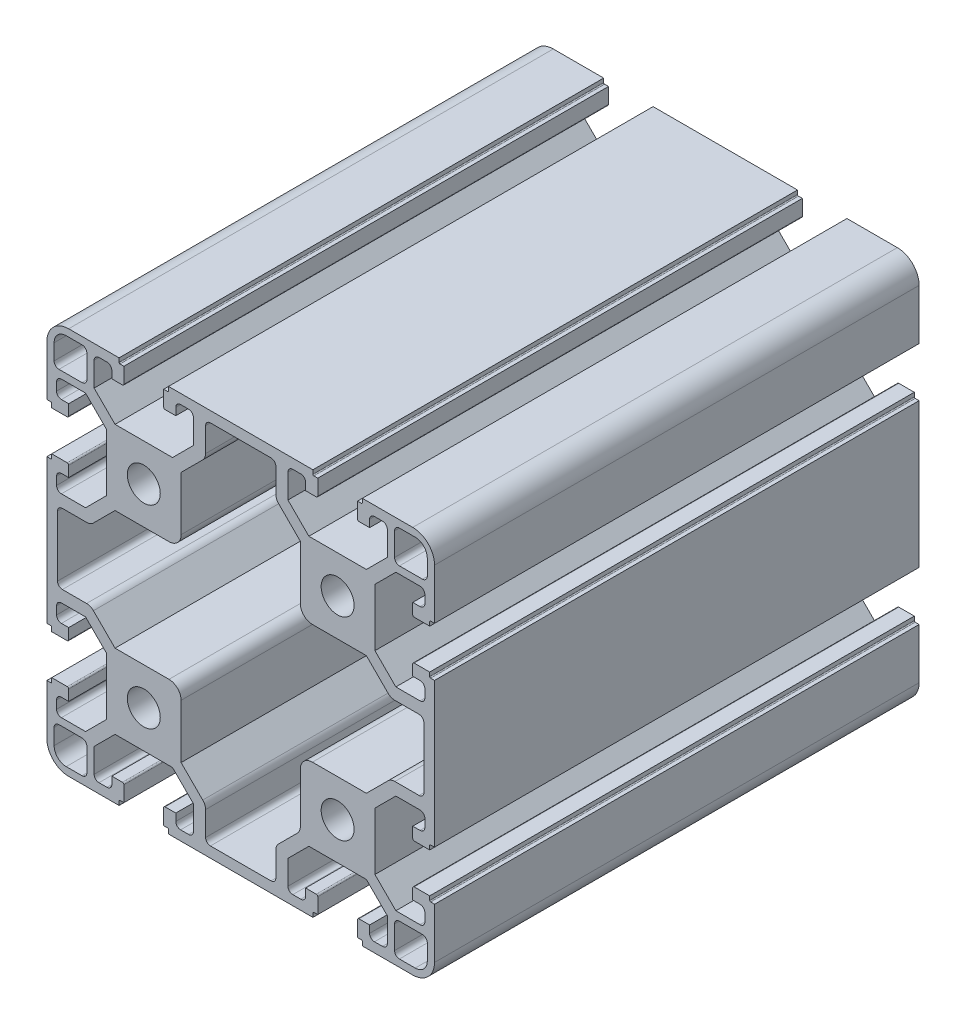
SolidWorks part; units mm, degrees
ref_plane "前视基准面" through (0, 0, 0) normal (0, 0, 1) x (1, 0, 0)
ref_plane "上视基准面" through (0, 0, 0) normal (0, 1, 0) x (1, 0, 0)
ref_plane "右视基准面" through (0, 0, 0) normal (1, 0, 0) x (0, 0, -1)
sketch "草图1" plane through (0, 0, 0) normal (0, 0, 1) x (1, 0, 0)
  line L0 (33.5347, -31.1296) -> (38.2887, -31.1296)
  line L1 (39.2887, -32.1296) -> (39.2887, -35.3836)
  line L2 (36.7887, -37.8836) -> (33.5347, -37.8836)
  line L3 (32.5347, -36.8836) -> (32.5347, -32.1296)
  line L4 (-30.9653, -32.1296) -> (-30.9653, -36.8836)
  line L5 (-31.9653, -37.8836) -> (-35.2193, -37.8836)
  line L6 (-37.7193, -35.3836) -> (-37.7193, -32.1296)
  line L7 (-36.7193, -31.1296) -> (-31.9653, -31.1296)
  line L8 (32.5347, 33.3704) -> (32.5347, 38.1244)
  line L9 (33.5347, 39.1244) -> (36.7887, 39.1244)
  line L10 (39.2887, 36.6244) -> (39.2887, 33.3704)
  line L11 (38.2887, 32.3704) -> (33.5347, 32.3704)
  line L12 (-31.9653, 32.3704) -> (-36.7193, 32.3704)
  line L13 (-37.7193, 33.3704) -> (-37.7193, 36.6244)
  line L14 (-35.2193, 39.1244) -> (-31.9653, 39.1244)
  line L15 (-30.9653, 38.1244) -> (-30.9653, 33.3704)
  line L16 (-11.5153, 26.5526) -> (-7.0511, 31.0168)
  line L17 (-6.4653, 32.4311) -> (-6.4653, 37.4204)
  line L18 (-5.4653, 38.4204) -> (7.0347, 38.4204)
  line L19 (8.0347, 37.4204) -> (8.0347, 32.4311)
  line L20 (8.6205, 31.0168) -> (13.0847, 26.5526)
  line L21 (13.0847, 26.5526) -> (13.0847, 15.4204)
  line L22 (15.5847, 12.9204) -> (26.717, 12.9204)
  line L23 (26.717, 12.9204) -> (31.1812, 8.4562)
  line L24 (32.5954, 7.8704) -> (37.5847, 7.8704)
  line L25 (38.5847, 6.8704) -> (38.5847, -5.6296)
  line L26 (37.5847, -6.6296) -> (32.5954, -6.6296)
  line L27 (31.1812, -7.2154) -> (26.717, -11.6796)
  line L28 (26.717, -11.6796) -> (15.5847, -11.6796)
  line L29 (13.0847, -14.1796) -> (13.0847, -24.4834)
  line L30 (12.4989, -25.8976) -> (8.6205, -29.776)
  line L31 (8.0347, -31.1903) -> (8.0347, -36.1796)
  line L32 (7.0347, -37.1796) -> (-5.4653, -37.1796)
  line L33 (-6.4653, -36.1796) -> (-6.4653, -31.1903)
  line L34 (-7.0511, -29.776) -> (-11.5153, -25.3118)
  line L35 (-11.5153, -25.3118) -> (-11.5153, -14.1796)
  line L36 (-14.0153, -11.6796) -> (-25.1475, -11.6796)
  line L37 (-25.1475, -11.6796) -> (-29.6117, -7.2154)
  line L38 (-31.0259, -6.6296) -> (-36.0153, -6.6296)
  line L39 (-37.0153, -5.6296) -> (-37.0153, 6.8704)
  line L40 (-36.0153, 7.8704) -> (-31.0259, 7.8704)
  line L41 (-29.6117, 8.4562) -> (-25.1475, 12.9204)
  line L42 (-25.1475, 12.9204) -> (-14.0153, 12.9204)
  line L43 (-11.5153, 15.4204) -> (-11.5153, 26.5526)
  line L44 (28.4847, 26.5526) -> (32.8025, 30.8704)
  line L45 (32.8025, 30.8704) -> (37.7847, 30.8704)
  line L46 (38.7847, 29.8704) -> (38.7847, 28.2204)
  line L47 (37.7847, 27.2204) -> (36.2847, 27.2204)
  line L48 (36.2847, 27.2204) -> (36.2847, 25.0204)
  line L49 (36.5847, 24.7204) -> (39.7847, 24.7204)
  line L50 (39.7847, 24.7204) -> (39.7847, 25.5204)
  line L51 (39.9847, 25.7204) -> (40.7847, 25.7204)
  line L52 (40.7847, 25.7204) -> (40.7847, 36.1204)
  line L53 (36.2847, 40.6204) -> (25.8847, 40.6204)
  line L54 (25.8847, 40.6204) -> (25.8847, 39.8204)
  line L55 (25.6847, 39.6204) -> (24.8847, 39.6204)
  line L56 (24.8847, 39.6204) -> (24.8847, 36.4204)
  line L57 (25.1847, 36.1204) -> (27.3847, 36.1204)
  line L58 (27.3847, 36.1204) -> (27.3847, 37.6204)
  line L59 (28.3847, 38.6204) -> (30.0347, 38.6204)
  line L60 (31.0347, 37.6204) -> (31.0347, 32.6382)
  line L61 (31.0347, 32.6382) -> (26.717, 28.3204)
  line L62 (26.717, 28.3204) -> (14.8525, 28.3204)
  line L63 (14.8525, 28.3204) -> (10.5347, 32.6382)
  line L64 (10.5347, 32.6382) -> (10.5347, 37.6204)
  line L65 (11.5347, 38.6204) -> (13.1847, 38.6204)
  line L66 (14.1847, 37.6204) -> (14.1847, 36.1204)
  line L67 (14.1847, 36.1204) -> (16.3847, 36.1204)
  line L68 (16.6847, 36.4204) -> (16.6847, 39.6204)
  line L69 (16.6847, 39.6204) -> (15.8847, 39.6204)
  line L70 (15.6847, 39.8204) -> (15.6847, 40.6204)
  line L71 (15.6847, 40.6204) -> (5.2847, 40.6204)
  line L72 (5.2847, 40.6204) -> (-3.7153, 40.6204)
  line L73 (-3.7153, 40.6204) -> (-14.1153, 40.6204)
  line L74 (-14.1153, 40.6204) -> (-14.1153, 39.8204)
  line L75 (-14.3153, 39.6204) -> (-15.1153, 39.6204)
  line L76 (-15.1153, 39.6204) -> (-15.1153, 36.4204)
  line L77 (-14.8153, 36.1204) -> (-12.6153, 36.1204)
  line L78 (-12.6153, 36.1204) -> (-12.6153, 37.6204)
  line L79 (-11.6153, 38.6204) -> (-9.9653, 38.6204)
  line L80 (-8.9653, 37.6204) -> (-8.9653, 32.6382)
  line L81 (-8.9653, 32.6382) -> (-13.283, 28.3204)
  line L82 (-13.283, 28.3204) -> (-25.1475, 28.3204)
  line L83 (-25.1475, 28.3204) -> (-29.4653, 32.6382)
  line L84 (-29.4653, 32.6382) -> (-29.4653, 37.6204)
  line L85 (-28.4653, 38.6204) -> (-26.8153, 38.6204)
  line L86 (-25.8153, 37.6204) -> (-25.8153, 36.1204)
  line L87 (-25.8153, 36.1204) -> (-23.6153, 36.1204)
  line L88 (-23.3153, 36.4204) -> (-23.3153, 39.6204)
  line L89 (-23.3153, 39.6204) -> (-24.1153, 39.6204)
  line L90 (-24.3153, 39.8204) -> (-24.3153, 40.6204)
  line L91 (-24.3153, 40.6204) -> (-34.7153, 40.6204)
  line L92 (-39.2153, 36.1204) -> (-39.2153, 25.7204)
  line L93 (-39.2153, 25.7204) -> (-38.4153, 25.7204)
  line L94 (-38.2153, 25.5204) -> (-38.2153, 24.7204)
  line L95 (-38.2153, 24.7204) -> (-35.0153, 24.7204)
  line L96 (-34.7153, 25.0204) -> (-34.7153, 27.2204)
  line L97 (-34.7153, 27.2204) -> (-36.2153, 27.2204)
  line L98 (-37.2153, 28.2204) -> (-37.2153, 29.8704)
  line L99 (-36.2153, 30.8704) -> (-31.233, 30.8704)
  line L100 (-31.233, 30.8704) -> (-26.9153, 26.5526)
  line L101 (-26.9153, 26.5526) -> (-26.9153, 14.6882)
  line L102 (-26.9153, 14.6882) -> (-31.233, 10.3704)
  line L103 (-31.233, 10.3704) -> (-36.2153, 10.3704)
  line L104 (-37.2153, 11.3704) -> (-37.2153, 13.0204)
  line L105 (-36.2153, 14.0204) -> (-34.7153, 14.0204)
  line L106 (-34.7153, 14.0204) -> (-34.7153, 16.2204)
  line L107 (-35.0153, 16.5204) -> (-38.2153, 16.5204)
  line L108 (-38.2153, 16.5204) -> (-38.2153, 15.7204)
  line L109 (-38.4153, 15.5204) -> (-39.2153, 15.5204)
  line L110 (-39.2153, 15.5204) -> (-39.2153, 5.1204)
  line L111 (-39.2153, 5.1204) -> (-39.2153, -3.8796)
  line L112 (-39.2153, -3.8796) -> (-39.2153, -14.2796)
  line L113 (-39.2153, -14.2796) -> (-38.4153, -14.2796)
  line L114 (-38.2153, -14.4796) -> (-38.2153, -15.2796)
  line L115 (-38.2153, -15.2796) -> (-35.0153, -15.2796)
  line L116 (-34.7153, -14.9796) -> (-34.7153, -12.7796)
  line L117 (-34.7153, -12.7796) -> (-36.2153, -12.7796)
  line L118 (-37.2153, -11.7796) -> (-37.2153, -10.1296)
  line L119 (-36.2153, -9.1296) -> (-31.233, -9.1296)
  line L120 (-31.233, -9.1296) -> (-26.9153, -13.4474)
  line L121 (-26.9153, -13.4474) -> (-26.9153, -25.3118)
  line L122 (-26.9153, -25.3118) -> (-31.233, -29.6296)
  line L123 (-31.233, -29.6296) -> (-36.2153, -29.6296)
  line L124 (-37.2153, -28.6296) -> (-37.2153, -26.9796)
  line L125 (-36.2153, -25.9796) -> (-34.7153, -25.9796)
  line L126 (-34.7153, -25.9796) -> (-34.7153, -23.7796)
  line L127 (-35.0153, -23.4796) -> (-38.2153, -23.4796)
  line L128 (-38.2153, -23.4796) -> (-38.2153, -24.2796)
  line L129 (-38.4153, -24.4796) -> (-39.2153, -24.4796)
  line L130 (-39.2153, -24.4796) -> (-39.2153, -34.8796)
  line L131 (-34.7153, -39.3796) -> (-24.3153, -39.3796)
  line L132 (-24.3153, -39.3796) -> (-24.3153, -38.5796)
  line L133 (-24.1153, -38.3796) -> (-23.3153, -38.3796)
  line L134 (-23.3153, -38.3796) -> (-23.3153, -35.1796)
  line L135 (-23.6153, -34.8796) -> (-25.8153, -34.8796)
  line L136 (-25.8153, -34.8796) -> (-25.8153, -36.3796)
  line L137 (-26.8153, -37.3796) -> (-28.4653, -37.3796)
  line L138 (-29.4653, -36.3796) -> (-29.4653, -31.3974)
  line L139 (-29.4653, -31.3974) -> (-25.1475, -27.0796)
  line L140 (-25.1475, -27.0796) -> (-13.283, -27.0796)
  line L141 (-13.283, -27.0796) -> (-8.9653, -31.3974)
  line L142 (-8.9653, -31.3974) -> (-8.9653, -36.3796)
  line L143 (-9.9653, -37.3796) -> (-11.6153, -37.3796)
  line L144 (-12.6153, -36.3796) -> (-12.6153, -34.8796)
  line L145 (-12.6153, -34.8796) -> (-14.8153, -34.8796)
  line L146 (-15.1153, -35.1796) -> (-15.1153, -38.3796)
  line L147 (-15.1153, -38.3796) -> (-14.3153, -38.3796)
  line L148 (-14.1153, -38.5796) -> (-14.1153, -39.3796)
  line L149 (-14.1153, -39.3796) -> (-3.7153, -39.3796)
  line L150 (-3.7153, -39.3796) -> (5.2847, -39.3796)
  line L151 (5.2847, -39.3796) -> (15.6847, -39.3796)
  line L152 (15.6847, -39.3796) -> (15.6847, -38.5796)
  line L153 (15.8847, -38.3796) -> (16.6847, -38.3796)
  line L154 (16.6847, -38.3796) -> (16.6847, -35.1796)
  line L155 (16.3847, -34.8796) -> (14.1847, -34.8796)
  line L156 (14.1847, -34.8796) -> (14.1847, -36.3796)
  line L157 (13.1847, -37.3796) -> (11.5347, -37.3796)
  line L158 (10.5347, -36.3796) -> (10.5347, -31.3974)
  line L159 (10.5347, -31.3974) -> (14.8525, -27.0796)
  line L160 (14.8525, -27.0796) -> (26.717, -27.0796)
  line L161 (26.717, -27.0796) -> (31.0347, -31.3974)
  line L162 (31.0347, -31.3974) -> (31.0347, -36.3796)
  line L163 (30.0347, -37.3796) -> (28.3847, -37.3796)
  line L164 (27.3847, -36.3796) -> (27.3847, -34.8796)
  line L165 (27.3847, -34.8796) -> (25.1847, -34.8796)
  line L166 (24.8847, -35.1796) -> (24.8847, -38.3796)
  line L167 (24.8847, -38.3796) -> (25.6847, -38.3796)
  line L168 (25.8847, -38.5796) -> (25.8847, -39.3796)
  line L169 (25.8847, -39.3796) -> (36.2847, -39.3796)
  line L170 (40.7847, -34.8796) -> (40.7847, -24.4796)
  line L171 (40.7847, -24.4796) -> (39.9847, -24.4796)
  line L172 (39.7847, -24.2796) -> (39.7847, -23.4796)
  line L173 (39.7847, -23.4796) -> (36.5847, -23.4796)
  line L174 (36.2847, -23.7796) -> (36.2847, -25.9796)
  line L175 (36.2847, -25.9796) -> (37.7847, -25.9796)
  line L176 (38.7847, -26.9796) -> (38.7847, -28.6296)
  line L177 (37.7847, -29.6296) -> (32.8025, -29.6296)
  line L178 (32.8025, -29.6296) -> (28.4847, -25.3118)
  line L179 (28.4847, -25.3118) -> (28.4847, -13.4474)
  line L180 (28.4847, -13.4474) -> (32.8025, -9.1296)
  line L181 (32.8025, -9.1296) -> (37.7847, -9.1296)
  line L182 (38.7847, -10.1296) -> (38.7847, -11.7796)
  line L183 (37.7847, -12.7796) -> (36.2847, -12.7796)
  line L184 (36.2847, -12.7796) -> (36.2847, -14.9796)
  line L185 (36.5847, -15.2796) -> (39.7847, -15.2796)
  line L186 (39.7847, -15.2796) -> (39.7847, -14.4796)
  line L187 (39.9847, -14.2796) -> (40.7847, -14.2796)
  line L188 (40.7847, -14.2796) -> (40.7847, -3.8796)
  line L189 (40.7847, -3.8796) -> (40.7847, 5.1204)
  line L190 (40.7847, 5.1204) -> (40.7847, 15.5204)
  line L191 (40.7847, 15.5204) -> (39.9847, 15.5204)
  line L192 (39.7847, 15.7204) -> (39.7847, 16.5204)
  line L193 (39.7847, 16.5204) -> (36.5847, 16.5204)
  line L194 (36.2847, 16.2204) -> (36.2847, 14.0204)
  line L195 (36.2847, 14.0204) -> (37.7847, 14.0204)
  line L196 (38.7847, 13.0204) -> (38.7847, 11.3704)
  line L197 (37.7847, 10.3704) -> (32.8025, 10.3704)
  line L198 (32.8025, 10.3704) -> (28.4847, 14.6882)
  line L199 (28.4847, 14.6882) -> (28.4847, 26.5526)
  arc A0 (39.2887, -32.1296) -> (38.2887, -31.1296) centre (38.2887, -32.1296) ccw
  arc A1 (36.7887, -37.8836) -> (39.2887, -35.3836) centre (36.7887, -35.3836) ccw
  arc A2 (32.5347, -36.8836) -> (33.5347, -37.8836) centre (33.5347, -36.8836) ccw
  arc A3 (33.5347, -31.1296) -> (32.5347, -32.1296) centre (33.5347, -32.1296) ccw
  arc A4 (-31.9653, -37.8836) -> (-30.9653, -36.8836) centre (-31.9653, -36.8836) ccw
  arc A5 (-37.7193, -35.3836) -> (-35.2193, -37.8836) centre (-35.2193, -35.3836) ccw
  arc A6 (-36.7193, -31.1296) -> (-37.7193, -32.1296) centre (-36.7193, -32.1296) ccw
  arc A7 (-30.9653, -32.1296) -> (-31.9653, -31.1296) centre (-31.9653, -32.1296) ccw
  circle A8 centre (20.7847, -19.3796) radius 3.4
  arc A9 (33.5347, 39.1244) -> (32.5347, 38.1244) centre (33.5347, 38.1244) ccw
  arc A10 (39.2887, 36.6244) -> (36.7887, 39.1244) centre (36.7887, 36.6244) ccw
  arc A11 (38.2887, 32.3704) -> (39.2887, 33.3704) centre (38.2887, 33.3704) ccw
  arc A12 (32.5347, 33.3704) -> (33.5347, 32.3704) centre (33.5347, 33.3704) ccw
  circle A13 centre (-19.2153, -19.3796) radius 3.4
  circle A14 centre (20.7847, 20.6204) radius 3.4
  arc A15 (-37.7193, 33.3704) -> (-36.7193, 32.3704) centre (-36.7193, 33.3704) ccw
  arc A16 (-35.2193, 39.1244) -> (-37.7193, 36.6244) centre (-35.2193, 36.6244) ccw
  arc A17 (-30.9653, 38.1244) -> (-31.9653, 39.1244) centre (-31.9653, 38.1244) ccw
  arc A18 (-31.9653, 32.3704) -> (-30.9653, 33.3704) centre (-31.9653, 33.3704) ccw
  circle A19 centre (-19.2153, 20.6204) radius 3.4
  arc A20 (-7.0511, 31.0168) -> (-6.4653, 32.4311) centre (-8.4653, 32.4311) ccw
  arc A21 (-5.4653, 38.4204) -> (-6.4653, 37.4204) centre (-5.4653, 37.4204) ccw
  arc A22 (8.0347, 37.4204) -> (7.0347, 38.4204) centre (7.0347, 37.4204) ccw
  arc A23 (8.0347, 32.4311) -> (8.6205, 31.0168) centre (10.0347, 32.4311) ccw
  arc A24 (13.0847, 15.4204) -> (15.5847, 12.9204) centre (15.5847, 15.4204) ccw
  arc A25 (31.1812, 8.4562) -> (32.5954, 7.8704) centre (32.5954, 9.8704) ccw
  arc A26 (38.5847, 6.8704) -> (37.5847, 7.8704) centre (37.5847, 6.8704) ccw
  arc A27 (37.5847, -6.6296) -> (38.5847, -5.6296) centre (37.5847, -5.6296) ccw
  arc A28 (32.5954, -6.6296) -> (31.1812, -7.2154) centre (32.5954, -8.6296) ccw
  arc A29 (15.5847, -11.6796) -> (13.0847, -14.1796) centre (15.5847, -14.1796) ccw
  arc A30 (12.4989, -25.8976) -> (13.0847, -24.4834) centre (11.0847, -24.4834) ccw
  arc A31 (8.6205, -29.776) -> (8.0347, -31.1903) centre (10.0347, -31.1903) ccw
  arc A32 (7.0347, -37.1796) -> (8.0347, -36.1796) centre (7.0347, -36.1796) ccw
  arc A33 (-6.4653, -36.1796) -> (-5.4653, -37.1796) centre (-5.4653, -36.1796) ccw
  arc A34 (-6.4653, -31.1903) -> (-7.0511, -29.776) centre (-8.4653, -31.1903) ccw
  arc A35 (-11.5153, -14.1796) -> (-14.0153, -11.6796) centre (-14.0153, -14.1796) ccw
  arc A36 (-29.6117, -7.2154) -> (-31.0259, -6.6296) centre (-31.0259, -8.6296) ccw
  arc A37 (-37.0153, -5.6296) -> (-36.0153, -6.6296) centre (-36.0153, -5.6296) ccw
  arc A38 (-36.0153, 7.8704) -> (-37.0153, 6.8704) centre (-36.0153, 6.8704) ccw
  arc A39 (-31.0259, 7.8704) -> (-29.6117, 8.4562) centre (-31.0259, 9.8704) ccw
  arc A40 (-14.0153, 12.9204) -> (-11.5153, 15.4204) centre (-14.0153, 15.4204) ccw
  arc A41 (38.7847, 29.8704) -> (37.7847, 30.8704) centre (37.7847, 29.8704) ccw
  arc A42 (37.7847, 27.2204) -> (38.7847, 28.2204) centre (37.7847, 28.2204) ccw
  arc A43 (36.2847, 25.0204) -> (36.5847, 24.7204) centre (36.5847, 25.0204) ccw
  arc A44 (39.9847, 25.7204) -> (39.7847, 25.5204) centre (39.9847, 25.5204) ccw
  arc A45 (40.7847, 36.1204) -> (36.2847, 40.6204) centre (36.2847, 36.1204) ccw
  arc A46 (25.6847, 39.6204) -> (25.8847, 39.8204) centre (25.6847, 39.8204) ccw
  arc A47 (24.8847, 36.4204) -> (25.1847, 36.1204) centre (25.1847, 36.4204) ccw
  arc A48 (28.3847, 38.6204) -> (27.3847, 37.6204) centre (28.3847, 37.6204) ccw
  arc A49 (31.0347, 37.6204) -> (30.0347, 38.6204) centre (30.0347, 37.6204) ccw
  arc A50 (11.5347, 38.6204) -> (10.5347, 37.6204) centre (11.5347, 37.6204) ccw
  arc A51 (14.1847, 37.6204) -> (13.1847, 38.6204) centre (13.1847, 37.6204) ccw
  arc A52 (16.3847, 36.1204) -> (16.6847, 36.4204) centre (16.3847, 36.4204) ccw
  arc A53 (15.6847, 39.8204) -> (15.8847, 39.6204) centre (15.8847, 39.8204) ccw
  arc A54 (-14.3153, 39.6204) -> (-14.1153, 39.8204) centre (-14.3153, 39.8204) ccw
  arc A55 (-15.1153, 36.4204) -> (-14.8153, 36.1204) centre (-14.8153, 36.4204) ccw
  arc A56 (-11.6153, 38.6204) -> (-12.6153, 37.6204) centre (-11.6153, 37.6204) ccw
  arc A57 (-8.9653, 37.6204) -> (-9.9653, 38.6204) centre (-9.9653, 37.6204) ccw
  arc A58 (-28.4653, 38.6204) -> (-29.4653, 37.6204) centre (-28.4653, 37.6204) ccw
  arc A59 (-25.8153, 37.6204) -> (-26.8153, 38.6204) centre (-26.8153, 37.6204) ccw
  arc A60 (-23.6153, 36.1204) -> (-23.3153, 36.4204) centre (-23.6153, 36.4204) ccw
  arc A61 (-24.3153, 39.8204) -> (-24.1153, 39.6204) centre (-24.1153, 39.8204) ccw
  arc A62 (-34.7153, 40.6204) -> (-39.2153, 36.1204) centre (-34.7153, 36.1204) ccw
  arc A63 (-38.2153, 25.5204) -> (-38.4153, 25.7204) centre (-38.4153, 25.5204) ccw
  arc A64 (-35.0153, 24.7204) -> (-34.7153, 25.0204) centre (-35.0153, 25.0204) ccw
  arc A65 (-37.2153, 28.2204) -> (-36.2153, 27.2204) centre (-36.2153, 28.2204) ccw
  arc A66 (-36.2153, 30.8704) -> (-37.2153, 29.8704) centre (-36.2153, 29.8704) ccw
  arc A67 (-37.2153, 11.3704) -> (-36.2153, 10.3704) centre (-36.2153, 11.3704) ccw
  arc A68 (-36.2153, 14.0204) -> (-37.2153, 13.0204) centre (-36.2153, 13.0204) ccw
  arc A69 (-34.7153, 16.2204) -> (-35.0153, 16.5204) centre (-35.0153, 16.2204) ccw
  arc A70 (-38.4153, 15.5204) -> (-38.2153, 15.7204) centre (-38.4153, 15.7204) ccw
  arc A71 (-38.2153, -14.4796) -> (-38.4153, -14.2796) centre (-38.4153, -14.4796) ccw
  arc A72 (-35.0153, -15.2796) -> (-34.7153, -14.9796) centre (-35.0153, -14.9796) ccw
  arc A73 (-37.2153, -11.7796) -> (-36.2153, -12.7796) centre (-36.2153, -11.7796) ccw
  arc A74 (-36.2153, -9.1296) -> (-37.2153, -10.1296) centre (-36.2153, -10.1296) ccw
  arc A75 (-37.2153, -28.6296) -> (-36.2153, -29.6296) centre (-36.2153, -28.6296) ccw
  arc A76 (-36.2153, -25.9796) -> (-37.2153, -26.9796) centre (-36.2153, -26.9796) ccw
  arc A77 (-34.7153, -23.7796) -> (-35.0153, -23.4796) centre (-35.0153, -23.7796) ccw
  arc A78 (-38.4153, -24.4796) -> (-38.2153, -24.2796) centre (-38.4153, -24.2796) ccw
  arc A79 (-39.2153, -34.8796) -> (-34.7153, -39.3796) centre (-34.7153, -34.8796) ccw
  arc A80 (-24.1153, -38.3796) -> (-24.3153, -38.5796) centre (-24.1153, -38.5796) ccw
  arc A81 (-23.3153, -35.1796) -> (-23.6153, -34.8796) centre (-23.6153, -35.1796) ccw
  arc A82 (-26.8153, -37.3796) -> (-25.8153, -36.3796) centre (-26.8153, -36.3796) ccw
  arc A83 (-29.4653, -36.3796) -> (-28.4653, -37.3796) centre (-28.4653, -36.3796) ccw
  arc A84 (-9.9653, -37.3796) -> (-8.9653, -36.3796) centre (-9.9653, -36.3796) ccw
  arc A85 (-12.6153, -36.3796) -> (-11.6153, -37.3796) centre (-11.6153, -36.3796) ccw
  arc A86 (-14.8153, -34.8796) -> (-15.1153, -35.1796) centre (-14.8153, -35.1796) ccw
  arc A87 (-14.1153, -38.5796) -> (-14.3153, -38.3796) centre (-14.3153, -38.5796) ccw
  arc A88 (15.8847, -38.3796) -> (15.6847, -38.5796) centre (15.8847, -38.5796) ccw
  arc A89 (16.6847, -35.1796) -> (16.3847, -34.8796) centre (16.3847, -35.1796) ccw
  arc A90 (13.1847, -37.3796) -> (14.1847, -36.3796) centre (13.1847, -36.3796) ccw
  arc A91 (10.5347, -36.3796) -> (11.5347, -37.3796) centre (11.5347, -36.3796) ccw
  arc A92 (30.0347, -37.3796) -> (31.0347, -36.3796) centre (30.0347, -36.3796) ccw
  arc A93 (27.3847, -36.3796) -> (28.3847, -37.3796) centre (28.3847, -36.3796) ccw
  arc A94 (25.1847, -34.8796) -> (24.8847, -35.1796) centre (25.1847, -35.1796) ccw
  arc A95 (25.8847, -38.5796) -> (25.6847, -38.3796) centre (25.6847, -38.5796) ccw
  arc A96 (36.2847, -39.3796) -> (40.7847, -34.8796) centre (36.2847, -34.8796) ccw
  arc A97 (39.7847, -24.2796) -> (39.9847, -24.4796) centre (39.9847, -24.2796) ccw
  arc A98 (36.5847, -23.4796) -> (36.2847, -23.7796) centre (36.5847, -23.7796) ccw
  arc A99 (38.7847, -26.9796) -> (37.7847, -25.9796) centre (37.7847, -26.9796) ccw
  arc A100 (37.7847, -29.6296) -> (38.7847, -28.6296) centre (37.7847, -28.6296) ccw
  arc A101 (38.7847, -10.1296) -> (37.7847, -9.1296) centre (37.7847, -10.1296) ccw
  arc A102 (37.7847, -12.7796) -> (38.7847, -11.7796) centre (37.7847, -11.7796) ccw
  arc A103 (36.2847, -14.9796) -> (36.5847, -15.2796) centre (36.5847, -14.9796) ccw
  arc A104 (39.9847, -14.2796) -> (39.7847, -14.4796) centre (39.9847, -14.4796) ccw
  arc A105 (39.7847, 15.7204) -> (39.9847, 15.5204) centre (39.9847, 15.7204) ccw
  arc A106 (36.5847, 16.5204) -> (36.2847, 16.2204) centre (36.5847, 16.2204) ccw
  arc A107 (38.7847, 13.0204) -> (37.7847, 14.0204) centre (37.7847, 13.0204) ccw
  arc A108 (37.7847, 10.3704) -> (38.7847, 11.3704) centre (37.7847, 11.3704) ccw
extrude "凸台-拉伸1" add sketch "草图1" along normal blind 100
